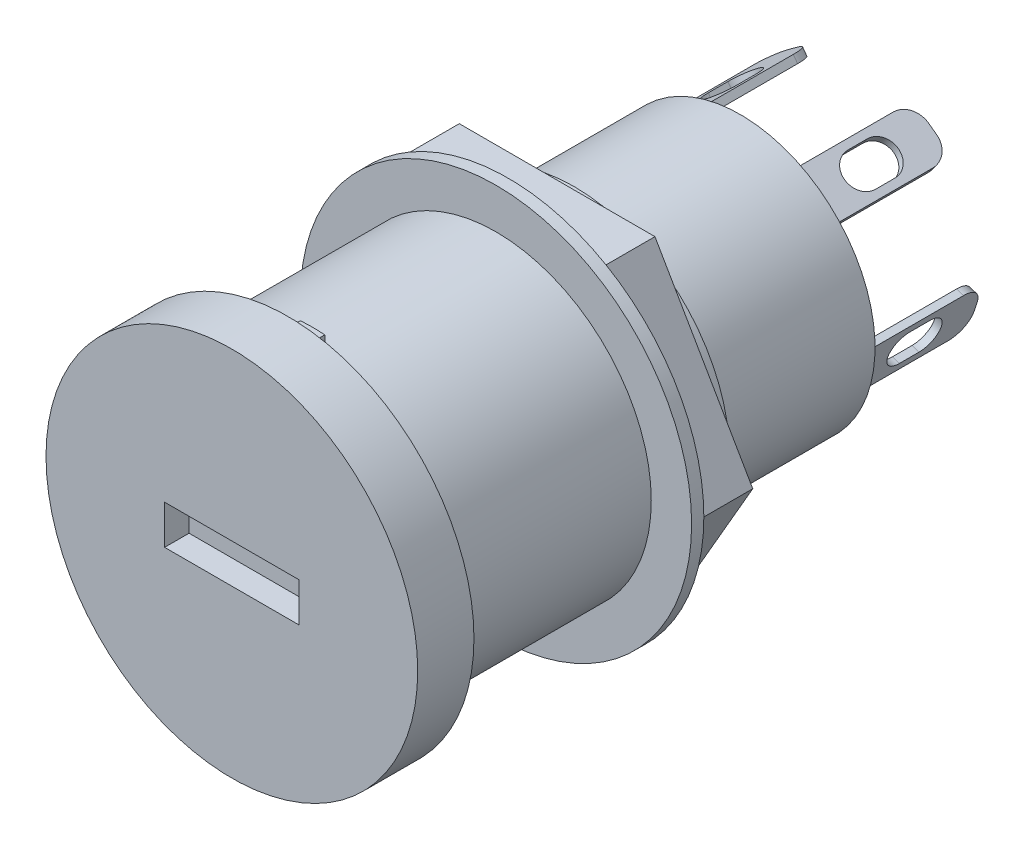
SolidWorks part; units mm, degrees
ref_plane "Front Plane" through (0, 0, 0) normal (0, 0, 1) x (1, 0, 0)
ref_plane "Top Plane" through (0, 0, 0) normal (0, 1, 0) x (1, 0, 0)
ref_plane "Right Plane" through (0, 0, 0) normal (1, 0, 0) x (0, 0, -1)
ref_plane "Plane1" through (0, 0, 0) normal (0, -1, 0) x (1, 0, 0)
sketch "Sketch1" plane through (0, 0, 0) normal (0, -1, 0) x (1, 0, 0)
  line L0 (7.6, 2.3) -> (0, 2.3)
  line L1 (0, 2.3) -> (0, -9)
  line L2 (0, -9) -> (8, -9)
  line L3 (8, -9) -> (8, -8.5)
  line L4 (8, -8.5) -> (6.35, -8.5)
  line L5 (6.35, -8.5) -> (6.35, 0)
  line L6 (6.35, 0) -> (7.6, 0)
  line L7 (7.6, 0) -> (7.6, 2.3)
  line L8 (0, 2.3) -> (0, -9) construction
revolve "Revolve1" add sketch "Sketch1" angle 360 about L8
sketch "Sketch2" plane through (0, 0, -9) normal (0, 0, -1) x (-1, 0, 0)
  line L0 (-4, -6.9282) -> (-8, 0)
  line L1 (-8, 0) -> (-4, 6.9282)
  line L2 (-4, 6.9282) -> (4, 6.9282)
  line L3 (4, 6.9282) -> (8, 0)
  line L4 (8, 0) -> (4, -6.9282)
  line L5 (4, -6.9282) -> (-4, -6.9282)
extrude "Boss-Extrude1" add sketch "Sketch2" along normal blind 2
sketch "Sketch3" plane through (0, 0, -11) normal (0, 0, -1) x (-1, 0, 0)
  circle A0 centre (0, 0) radius 6.35
extrude "Boss-Extrude2" add sketch "Sketch3" along normal blind 0.7
sketch "Sketch4" plane through (0, 0, -11.7) normal (0, 0, -1) x (-1, 0, 0)
  circle A0 centre (0, 0) radius 6.35
extrude "Boss-Extrude3" add sketch "Sketch4" along normal blind 0.4907 draft 60
sketch "Sketch5" plane through (0, 0, -12.1907) normal (0, 0, -1) x (-1, 0, 0)
  circle A0 centre (0, 0) radius 5.5
extrude "Boss-Extrude4" add sketch "Sketch5" along normal blind 6.3093
sketch "Sketch6" plane through (0, 0, -18.5) normal (0, 0, -1) x (-1, 0, 0)
  line L0 (-4.9216, -0.5477) -> (-4.6363, -0.455)
  line L1 (-4.6363, -0.455) -> (-4.0183, -2.3571)
  line L2 (-4.0183, -2.3571) -> (-4.3036, -2.4498)
  line L3 (-4.3036, -2.4498) -> (-4.9216, -0.5477)
extrude "Boss-Extrude5" add sketch "Sketch6" along normal blind 5
sketch "Sketch7" plane through (4.3273, -1.406, 0) normal (-0.9511, 0.309, 0) x (0, 0, 1)
  line L0 (-21.4, -0.7) -> (-20.6, -0.7)
  line L1 (-20.6, 0.7) -> (-21.4, 0.7)
  arc A0 (-21.4, 0.7) -> (-21.4, -0.7) centre (-21.4, 0) ccw
  arc A1 (-20.6, -0.7) -> (-20.6, 0.7) centre (-20.6, 0) ccw
extrude "Cut-Extrude1" cut sketch "Sketch7" against normal through all
sketch "Sketch8" plane through (0, 0, -18.5) normal (0, 0, -1) x (-1, 0, 0)
  line L0 (-3.4834, 3.0932) -> (-3.6598, 3.3359)
  line L1 (-3.6598, 3.3359) -> (-2.0417, 4.5115)
  line L2 (-2.0417, 4.5115) -> (-1.8654, 4.2688)
  line L3 (-1.8654, 4.2688) -> (-3.4834, 3.0932)
extrude "Boss-Extrude6" add sketch "Sketch8" along normal blind 5
sketch "Sketch9" plane through (2.6744, 3.681, 0) normal (-0.5878, -0.809, 0) x (0.809, -0.5878, 0)
  line L0 (0.7, -21.4) -> (0.7, -20.6)
  line L1 (-0.7, -20.6) -> (-0.7, -21.4)
  arc A0 (-0.7, -21.4) -> (0.7, -21.4) centre (0, -21.4) ccw
  arc A1 (0.7, -20.6) -> (-0.7, -20.6) centre (0, -20.6) ccw
extrude "Cut-Extrude2" cut sketch "Sketch9" against normal through all
sketch "Sketch10" plane through (0, 0, -18.5) normal (0, 0, -1) x (-1, 0, 0)
  line L0 (4.6363, -0.455) -> (4.9216, -0.5477)
  line L1 (4.9216, -0.5477) -> (4.3036, -2.4498)
  line L2 (4.3036, -2.4498) -> (4.0183, -2.3571)
  line L3 (4.0183, -2.3571) -> (4.6363, -0.455)
extrude "Boss-Extrude7" add sketch "Sketch10" along normal blind 5
sketch "Sketch11" plane through (-4.6126, -1.4987, 0) normal (-0.9511, -0.309, 0) x (0, 0, 1)
  line L0 (-20.6, 0.7) -> (-21.4, 0.7)
  line L1 (-21.4, -0.7) -> (-20.6, -0.7)
  arc A0 (-20.6, -0.7) -> (-20.6, 0.7) centre (-20.6, 0) ccw
  arc A1 (-21.4, 0.7) -> (-21.4, -0.7) centre (-21.4, 0) ccw
extrude "Cut-Extrude3" cut sketch "Sketch11" against normal through all
sketch "Sketch12" plane through (0, 0, -18.5) normal (0, 0, -1) x (-1, 0, 0)
  line L0 (1.8654, 4.2688) -> (2.0417, 4.5115)
  line L1 (2.0417, 4.5115) -> (3.6598, 3.3359)
  line L2 (3.6598, 3.3359) -> (3.4834, 3.0932)
  line L3 (3.4834, 3.0932) -> (1.8654, 4.2688)
extrude "Boss-Extrude8" add sketch "Sketch12" along normal blind 5
sketch "Sketch13" plane through (-2.8508, 3.9237, 0) normal (-0.5878, 0.809, 0) x (-0.809, -0.5878, 0)
  line L0 (-0.7, -20.6) -> (-0.7, -21.4)
  line L1 (0.7, -21.4) -> (0.7, -20.6)
  arc A0 (0.7, -20.6) -> (-0.7, -20.6) centre (0, -20.6) ccw
  arc A1 (-0.7, -21.4) -> (0.7, -21.4) centre (0, -21.4) ccw
extrude "Cut-Extrude4" cut sketch "Sketch13" against normal through all
ref_plane "Plane2" through (0, -1.5875, 0) normal (0, 1, 0) x (1, 0, 0)
sketch "Sketch14" plane through (0, -1.5875, 0) normal (0, 1, 0) x (1, 0, 0)
  line L0 (-0.5, 1) -> (0.5, 1)
  line L1 (0.5, 1) -> (0.5, 0)
  line L2 (0.5, 0) -> (-0.5, 0)
  line L3 (-0.5, 0) -> (-0.5, 1)
extrude "Boss-Extrude9" add sketch "Sketch14" along normal blind 0.3697 from surface starting at face at (-6.35, 0, 0)
fillet "Fillet1" radius 0.8 8 edges at (-3.5716, 3.2146, -23.5) (-4.1609, -2.4034, -23.5) (-4.779, -0.5013, -23.5) (4.1609, -2.4034, -23.5) (-1.9536, 4.3902, -23.5) (3.5716, 3.2146, -23.5) (4.779, -0.5013, -23.5) (1.9536, 4.3902, -23.5)
sketch "Sketch15" plane through (0, 0, 2.3) normal (0, 0, 1) x (1, 0, 0)
  line L1 (-2.75, 0.8) -> (2.75, 0.8)
  line L2 (-2.75, 0.8) -> (-2.75, -0.8)
  line L3 (-2.75, -0.8) -> (2.75, -0.8)
  line L4 (2.75, 0.8) -> (2.75, -0.8)
  point P4 (0, 0.8)
  point P6 (2.75, 0)
  dimension "D1" = 1.6
  dimension "D2" = 5.5
extrude "Cut-Extrude5" cut sketch "Sketch15" against normal blind 1
